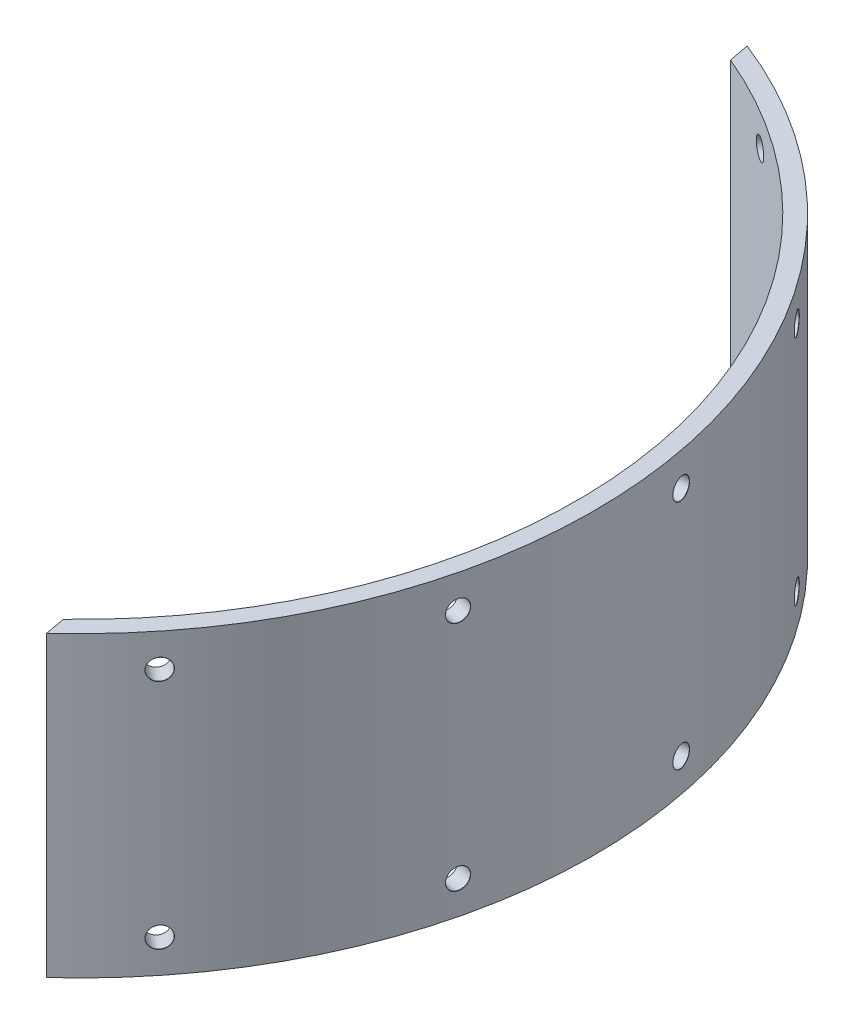
SolidWorks part; units mm, degrees
material "PE High Density"
ref_plane "Front Plane" through (0, 0, 0) normal (0, 0, 1) x (1, 0, 0)
ref_plane "Top Plane" through (0, 0, 0) normal (0, 1, 0) x (1, 0, 0)
ref_plane "Right Plane" through (0, 0, 0) normal (1, 0, 0) x (0, 0, -1)
sketch "Sketch2" plane through (0, 0, 0) normal (0, 1, 0) x (1, 0, 0)
  line L0 (-1000, 0) -> (49000, 0) construction
  line L1 (0, -1000) -> (0, 49000) construction
  line L12 (23.2112, 55.3285) -> (22.7568, 57.7931)
  line L15 (24.5438, 48.0999) -> (23.2112, 55.3285) construction
  line L16 (23.2112, 55.3285) -> (22.3025, 60.2578) construction
  line L17 (40.0819, -36.1862) -> (41.4145, -43.4147) construction
  line L19 (38.9265, -29.9189) -> (43.3602, -53.9693) construction
  line L20 (41.4145, -43.4147) -> (41.8688, -45.8794)
  arc A0 (60, 0) -> (44.2347, 40.5375) centre (0, 0) ccw construction
  arc A2 (41.8688, -45.8794) -> (22.7568, 57.7931) centre (0, 0) ccw
  arc A6 (41.4145, -43.4147) -> (23.2112, 55.3285) centre (0, 0) ccw construction
  arc A7 (23.2112, 55.3285) -> (41.4145, -43.4147) centre (0, 0) cw construction
  arc A8 (32.9354, 43.0769) -> (32.9354, -42.8233) centre (0.2049, 0.1268) cw construction
  arc A9 (41.4145, -43.4147) -> (23.2112, 55.3285) centre (0, 0) ccw
extrude "Boss-Extrude1" add sketch "Sketch2" along normal blind 36
sketch "Sketch6" plane through (23.9569, -74.6027, 75.8672) normal (0, 1, 0) x (0.9834, 0, -0.1813)
  line L0 (23.0518, 36.1) -> (23.0518, 28.7497) construction
  line L1 (23.0518, 129.1568) -> (23.0518, 121.8064) construction
  line L2 (23.0518, 36.1) -> (23.0518, 28.7497) construction
  arc A0 (23.0518, 121.8064) -> (23.0518, 36.1) centre (-9.8056, 78.9532) cw construction
  arc A1 (23.0518, 28.7497) -> (23.0518, 129.1568) centre (-9.8056, 78.9532) ccw construction
  arc A2 (23.0518, 28.7497) -> (23.0518, 129.1568) centre (-9.8056, 78.9532) ccw construction
hole_wizard "Tap Drill for M3x0.5 Tap2" positions "3DSketch2" profile "Sketch10" hole size "M3x0.5" standard "ANSI Metric"
sketch3d "3DSketch2"
  line L0 (41.8688, 36, 45.8794) -> (41.8688, 0, 45.8794) construction
  line L1 (22.7568, 36, -57.7931) -> (22.7568, 0, -57.7931) construction
  point P5 (48.47, 4, 38.8404)
  point P10 (60.349, 4, 14.6942)
  point P22 (61.0237, 4, -11.5771)
  point P24 (50.7622, 4, -35.7927)
  point P26 (31.434, 4, -53.5707)
  point P28 (31.434, 32.1205, -53.5707)
  point P30 (50.7622, 32, -35.7927)
  point P32 (61.0237, 32, -11.5771)
  point P34 (60.349, 32, 14.6942)
  point P36 (48.47, 32, 38.8404)
  dimension "D1" = 9.65
  dimension "D2" = 26.91
  dimension "D3" = 26.28
  dimension "D4" = 4
  dimension "D5" = 4
  dimension "D6" = 4
  dimension "D7" = 4
  dimension "D8" = 26.3
  dimension "D9" = 4
  dimension "D10" = 26.3
  dimension "D11" = 4
  dimension "D12" = 4
  dimension "D13" = 4
  dimension "D14" = 26.28
  dimension "D15" = 9.65
  dimension "D16" = 4
  dimension "D17" = 26.91
  dimension "D18" = 9.65
  dimension "D19" = 9.65
sketch "Sketch10" plane through (48.47, 4, 38.8404) normal (0, 1, 0) x (0.6253, 0, -0.7804)
  line L0 (0, 0) -> (0, 10.7511)
  line L1 (0, 10.7511) -> (1.25, 10)
  line L2 (1.25, 10) -> (1.25, 0.025)
  line L3 (1.25, 0.025) -> (1.275, 0)
  line L5 (1.275, 0) -> (0, 0)
  line L6 (-1.25, 0.025) -> (-1.275, 0) construction
  line L10 (0, 10.7511) -> (-1.25, 10) construction
  line L11 (0, -6.35) -> (0, 107.95) construction
  dimension "Hole Dia." = 2.5
  dimension "Hole Depth" = 10
  dimension "Near C'Sink Dia." = 2.55
  dimension "Near C'Sink Angle" = 90
  dimension "Drill Angle" = 118
